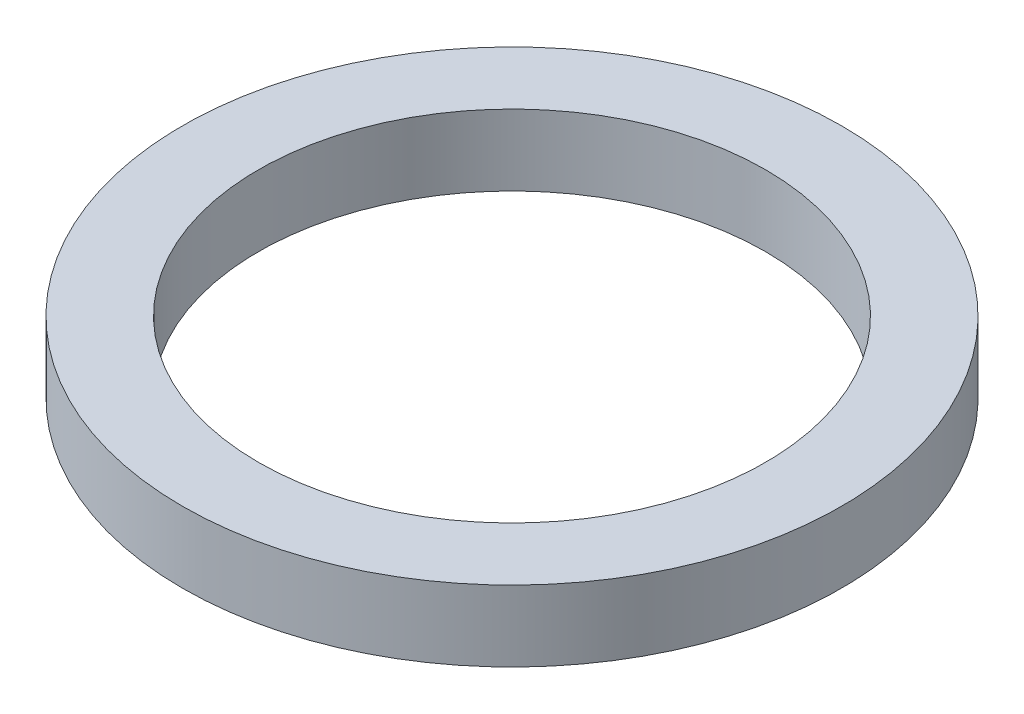
SolidWorks part; units mm, degrees
material "不锈钢 (铁素体)"
ref_plane "前视基准面" through (0, 0, 0) normal (0, 0, 1) x (1, 0, 0)
ref_plane "上视基准面" through (0, 0, 0) normal (0, 1, 0) x (1, 0, 0)
ref_plane "右视基准面" through (0, 0, 0) normal (1, 0, 0) x (0, 0, -1)
sketch "草图1" plane through (0, 0, 0) normal (0, 1, 0) x (1, 0, 0)
  circle A0 centre (0, 0) radius 25
  circle A1 centre (0, 0) radius 32.5
  dimension "D1" = 50
  dimension "D2" = 65
extrude "凸台-拉伸1" add sketch "草图1" along normal blind 7
